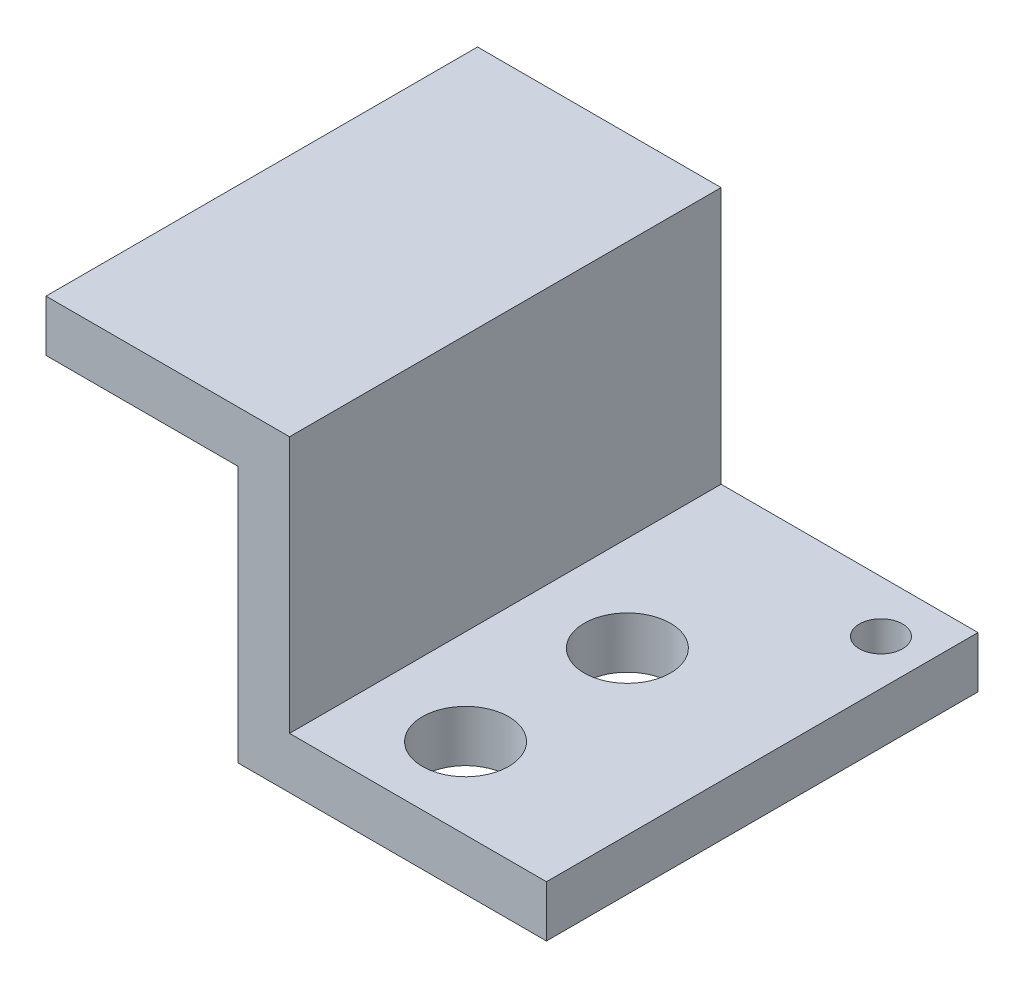
SolidWorks part; units mm, degrees
material "6061 Alloy"
ref_plane "Front Plane" through (0, 0, 0) normal (0, 0, 1) x (1, 0, 0)
ref_plane "Top Plane" through (0, 0, 0) normal (0, 1, 0) x (1, 0, 0)
ref_plane "Right Plane" through (0, 0, 0) normal (1, 0, 0) x (0, 0, -1)
sketch "Sketch1" plane through (0, 0, 0) normal (0, 0, 1) x (1, 0, 0)
  line L0 (0, -11.9062) -> (0, 11.9062) construction
  line L1 (0, 11.9062) -> (-26.1938, 11.9062) construction
  line L2 (0, -11.9062) -> (26.1938, -11.9062) construction
  line L3 (2.3812, -9.525) -> (26.1938, -9.525) construction
  line L4 (2.3812, -9.525) -> (2.3812, 14.2875) construction
  line L5 (2.3812, 14.2875) -> (-26.1938, 14.2875) construction
  line L6 (-2.3812, -14.2875) -> (26.1938, -14.2875) construction
  line L7 (-2.3812, -14.2875) -> (-2.3812, 9.525) construction
  line L8 (-2.3812, 9.525) -> (-26.1938, 9.525) construction
  line L9 (-26.1938, 14.2875) -> (-26.1938, 9.525) construction
  line L10 (26.1938, -9.525) -> (26.1938, -14.2875) construction
  point P4 (0, 0)
  dimension "Leg Width" = 28.575
  dimension "Outside Height" = 28.575
  dimension "Wall Thickness" = 4.7625
sketch "Sketch2" plane through (0, 0, 0) normal (1, 0, 0) x (0, 0, -1)
  line L0 (152.4, 0) -> (-152.4, 0) construction
  line L1 (0, 0) -> (0, 14.2875) construction
  line L2 (-152.4, 0) -> (-152.4, 14.2875) construction
  line L3 (152.4, 0) -> (152.4, 14.2875) construction
  point P0 (-114.3, 0)
  point P3 (114.3, 0)
  point P4 (0, 0)
  dimension "D1" = 228.6
  dimension "Length" = 304.8
sketch "Sketch3" plane through (0, 0, 0) normal (0, 0, 1) x (1, 0, 0)
  line L0 (26.1938, -9.525) -> (26.1938, -14.2875) construction
  line L1 (2.3812, -9.525) -> (26.1938, -9.525) construction
  line L2 (-2.3812, -14.2875) -> (26.1938, -14.2875) construction
  line L3 (-2.3812, -14.2875) -> (-2.3812, 9.525) construction
  line L4 (2.3812, -9.525) -> (2.3812, 14.2875) construction
  line L5 (2.3812, 14.2875) -> (-26.1938, 14.2875) construction
  line L6 (-26.1938, 14.2875) -> (-26.1938, 9.525) construction
  line L7 (-2.3812, 9.525) -> (-26.1938, 9.525) construction
  line L8 (26.1938, -9.525) -> (26.1938, -14.2875)
  line L9 (2.3812, -9.525) -> (26.1938, -9.525)
  line L10 (-2.3812, -14.2875) -> (26.1938, -14.2875)
  line L11 (-2.3812, -14.2875) -> (-2.3812, 9.525)
  line L12 (2.3812, -9.525) -> (2.3812, 14.2875)
  line L13 (2.3812, 14.2875) -> (-26.1938, 14.2875)
  line L14 (-26.1938, 14.2875) -> (-26.1938, 9.525)
  line L15 (-2.3812, 9.525) -> (-26.1938, 9.525)
extrude "Boss-Extrude1" add sketch "Sketch3" along normal blind 40
sketch "Sketch4" plane through (0, 14.2875, 0) normal (0, 1, 0) x (1, 0, 0)
  line L1 (-26.1938, -40) -> (-20.1937, -40)
  line L3 (2.3812, -40) -> (-26.1938, -40) construction
  line L5 (-26.1938, 0) -> (-26.1938, -40)
  line L8 (-26.1938, 0) -> (-20.1938, 0)
  line L9 (-20.1938, 0) -> (-20.1937, -40)
extrude "Cut-Extrude1" cut sketch "Sketch4" against normal up to surface (4.7625 mm away) up to face at (-14.2875, 9.525, 20)
sketch "Sketch5" plane through (0, -14.2875, 0) normal (0, -1, 0) x (1, 0, 0)
  line L4 (-2.3812, 40) -> (26.1938, 40) construction
  line L5 (-2.3812, 0) -> (26.1938, 0) construction
  line L6 (-2.3812, 40) -> (-2.3812, 0) construction
  circle A4 centre (22.0033, 4.8026) radius 2
  circle A5 centre (11.1937, 17.5) radius 4
  circle A6 centre (11.1937, 32.5) radius 4
  dimension "D1" = 7.5
  dimension "D2" = 17.5
  dimension "D3" = 24.3846
  dimension "D4" = 4.8026
extrude "Cut-Extrude2" cut sketch "Sketch5" against normal up to surface (4.7625 mm away) up to face at (14.2875, -9.525, 20)
equation "\"D1@Sketch2\"=\"Length@Sketch2\"*0.75"
